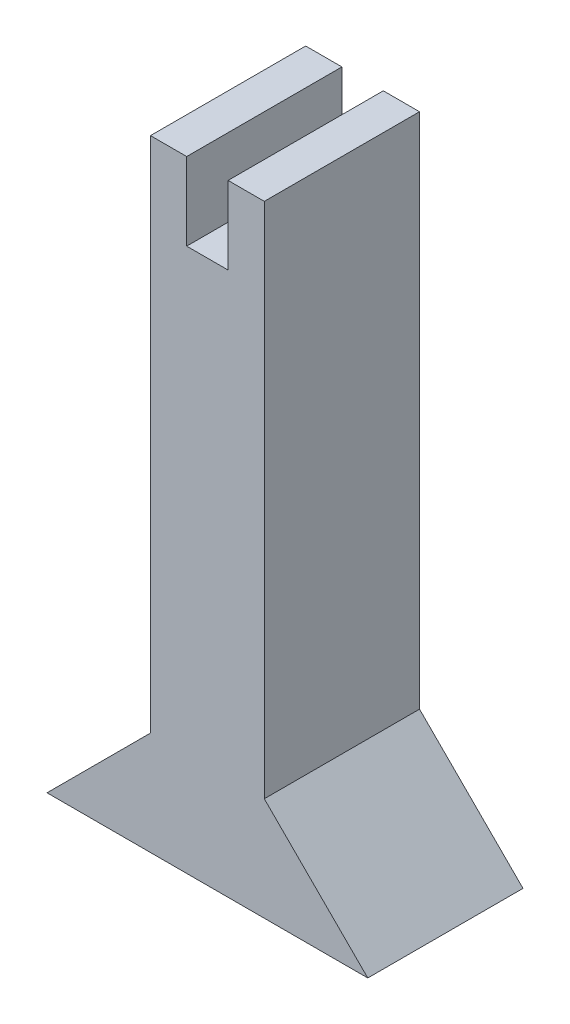
SolidWorks part; units mm, degrees
ref_plane "Front" through (0, 0, 0) normal (0, 0, 1) x (1, 0, 0)
ref_plane "Top" through (0, 0, 0) normal (0, 1, 0) x (1, 0, 0)
ref_plane "Right" through (0, 0, 0) normal (1, 0, 0) x (0, 0, -1)
sketch "Sketch1" plane through (0, 0, 0) normal (0, 0, 1) x (1, 0, 0)
  line L0 (0, 0) -> (8, 0)
  line L1 (0, 0) -> (0, 15)
  line L2 (8, 0) -> (8, 15)
  line L3 (4, 0) -> (4, 51.6296) construction
  line L4 (0, 15) -> (-7, 15)
  line L5 (-7, 15) -> (-7, -105)
  line L6 (-7, -105) -> (15, -105)
  line L7 (15, 15) -> (15, -105)
  line L8 (8, 15) -> (15, 15)
  point P11 (4, -105)
  dimension "D1" = 8
  dimension "D2" = 7
  dimension "D3" = 120
  dimension "D4" = 15
extrude "Boss-Extrude1" add sketch "Sketch1" along normal blind 30
sketch "Sketch2" plane through (0, 0, 30) normal (0, 0, 1) x (1, 0, 0)
  line L0 (15, -85) -> (35, -105)
  line L1 (15, -105) -> (15, 15) construction
  line L2 (35, -105) -> (15, -105)
  line L3 (15, -105) -> (15, -85)
  dimension "D1" = 20
  dimension "D2" = 20
extrude "Boss-Extrude2" add sketch "Sketch2" against normal up to surface (30 mm away) up to face at (4, -18.75, 0)
ref_plane "Plane1" through (4, 0, 0) normal (-1, 0, 0) x (0, 0, 1)
mirror "Mirror1" about plane through (4, 0, 0) normal (-1, 0, 0) of "Boss-Extrude2"
